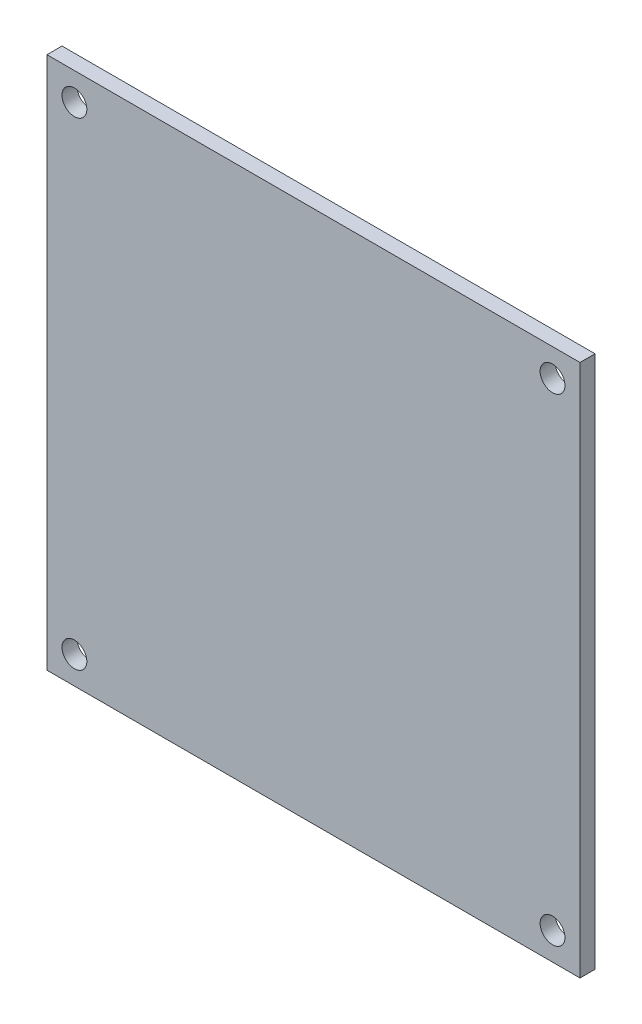
SolidWorks part; units mm, degrees
material "Acrylic (Medium-high impact)"
ref_plane "Front Plane" through (0, 0, 0) normal (0, 0, 1) x (1, 0, 0)
ref_plane "Top Plane" through (0, 0, 0) normal (0, 1, 0) x (1, 0, 0)
ref_plane "Right Plane" through (0, 0, 0) normal (1, 0, 0) x (0, 0, -1)
sketch "Sketch1" plane through (0, 0, 0) normal (0, 0, 1) x (1, 0, 0)
  line L0 (167.875, 167.875) -> (9.125, 9.125) construction
  line L1 (0, 0) -> (177, 0)
  line L2 (0, 0) -> (0, 177)
  line L3 (0, 177) -> (177, 177)
  line L4 (177, 0) -> (177, 177)
  line L5 (9.125, 9.125) -> (167.875, 9.125) construction
  line L6 (9.125, 9.125) -> (9.125, 167.875) construction
  line L7 (9.125, 167.875) -> (167.875, 167.875) construction
  line L8 (167.875, 9.125) -> (167.875, 167.875) construction
  line L9 (5, 9.125) -> (0, 9.125) construction
  line L10 (163.6459, 1.8) -> (159.4168, 9.125)
  line L11 (17.5832, 9.125) -> (13.3541, 16.45)
  line L12 (13.3541, 16.45) -> (4.8959, 16.45)
  line L13 (4.8959, 16.45) -> (0.6668, 9.125)
  line L14 (0.6668, 9.125) -> (4.8959, 1.8)
  line L15 (4.8959, 1.8) -> (13.3541, 1.8)
  line L16 (13.3541, 1.8) -> (17.5832, 9.125)
  line L17 (172.1041, 1.8) -> (163.6459, 1.8)
  line L18 (176.3332, 9.125) -> (172.1041, 1.8)
  line L19 (172.1041, 16.45) -> (176.3332, 9.125)
  line L20 (9.125, 88.5) -> (0, 88.5) construction
  line L21 (88.5, 9.125) -> (88.5, 0) construction
  line L22 (163.6459, 16.45) -> (172.1041, 16.45)
  line L23 (159.4168, 9.125) -> (163.6459, 16.45)
  line L24 (172.1041, 160.55) -> (176.3332, 167.875)
  line L25 (176.3332, 167.875) -> (172.1041, 175.2)
  line L26 (172.1041, 175.2) -> (163.6459, 175.2)
  line L27 (163.6459, 175.2) -> (159.4168, 167.875)
  line L28 (159.4168, 167.875) -> (163.6459, 160.55)
  line L29 (163.6459, 160.55) -> (172.1041, 160.55)
  line L30 (4.8959, 160.55) -> (0.6668, 167.875)
  line L31 (0.6668, 167.875) -> (4.8959, 175.2)
  line L32 (4.8959, 175.2) -> (13.3541, 175.2)
  line L33 (13.3541, 175.2) -> (17.5832, 167.875)
  line L34 (17.5832, 167.875) -> (13.3541, 160.55)
  line L35 (13.3541, 160.55) -> (4.8959, 160.55)
  circle A0 centre (9.125, 9.125) radius 4.125
  circle A1 centre (9.125, 9.125) radius 7.325 construction
  circle A2 centre (167.875, 9.125) radius 4.125
  circle A3 centre (167.875, 167.875) radius 4.125
  circle A4 centre (88.5, 88.5) radius 2.5
  circle A5 centre (9.125, 167.875) radius 4.125
  text T0 "                 Base Plate" font "Century Gothic" height 1.5
  point P47 (88.5, 167.875)
  dimension "D2" = 8.25
  dimension "D3" = 5
  dimension "D4" = 5
  dimension "D1" = 158.75
  dimension "D5" = 14.65
extrude "Boss-Extrude1" add sketch "Sketch1" along normal blind 5 contours L1 L4 L3 L2 A4 L10 L23 L22 L19 L18 L17 L16 L15 L14 L13 L12 L11 L29 L28 L27 L26 L25 L24 L34 L35 L30 L31 L32 L33 | L35 L34 L33 L32 L31 L30 A5 | L15 L16 L11 L12 L13 L14 A0 | L23 L10 L17 L18 L19 L22 A2 | L28 L29 L24 L25 L26 L27 A3 | A4
